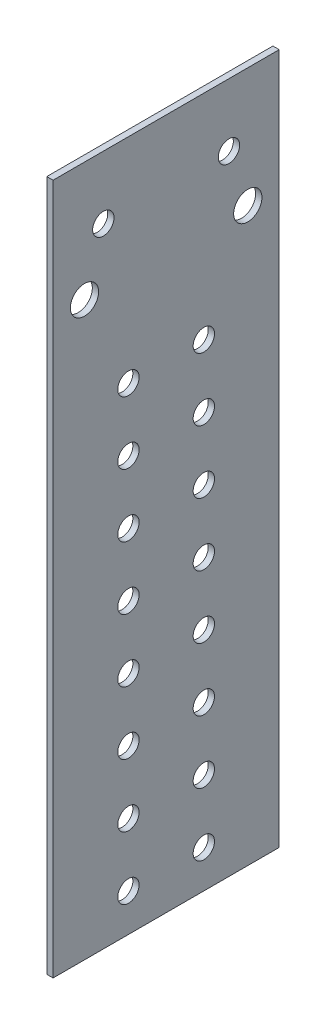
SolidWorks part; units mm, degrees
material "PVC 0.007 Plasticized"
ref_plane "Front Plane" through (0, 0, 0) normal (0, 0, 1) x (1, 0, 0)
ref_plane "Top Plane" through (0, 0, 0) normal (0, 1, 0) x (1, 0, 0)
ref_plane "Right Plane" through (0, 0, 0) normal (1, 0, 0) x (0, 0, -1)
sketch "Sketch1" plane through (0, 0, 0) normal (1, 0, 0) x (0, 0, -1)
  line L1 (-18, 0) -> (18, 0)
  line L2 (-18, 0) -> (-18, -110)
  line L3 (-18, -110) -> (18, -110)
  line L4 (18, 0) -> (18, -110)
  line L5 (-18, 0) -> (18, -110) construction
  line L6 (-18, -110) -> (18, 0) construction
  point P4 (0, -55)
  point P5 (0, 0)
  dimension "D1" = 110
  dimension "D2" = 36
extrude "Boss-Extrude1" add sketch "Sketch1" along normal blind 1 contours L2 L3 L4 L1
hole_wizard "M3 Clearance Hole1" positions "Sketch2" profile "Sketch3" hole size "M3" standard "ISO" end condition through all
sketch "Sketch2" plane through (0, 0, 0) normal (-1, 0, 0) x (0, 0, 1)
  point P0 (-10, -10)
  point P3 (10, -10)
sketch "Sketch3" plane through (0, -10, -10) normal (0, 1, 0) x (0, 0, 1)
  line L0 (0, 0) -> (0, 1)
  line L1 (0, 1) -> (1.7, 1)
  line L2 (1.7, 1) -> (1.7, 0)
  line L5 (1.7, 0) -> (0, 0)
  line L11 (0, -6.35) -> (0, 107.95) construction
  dimension "Thru Hole Dia." = 3.4
  dimension "Thru Hole Depth" = 1
hole_wizard "M4 Clearance Hole1" positions "Sketch4" profile "Sketch5" hole size "M4" standard "ISO" end condition through all
sketch "Sketch4" plane through (0, 0, 0) normal (-1, 0, 0) x (0, 0, 1)
  point P0 (-13, -19)
  point P3 (13, -19)
sketch "Sketch5" plane through (0, -19, -13) normal (0, 1, 0) x (0, 0, 1)
  line L0 (0, 0) -> (0, 1)
  line L1 (0, 1) -> (2.25, 1)
  line L2 (2.25, 1) -> (2.25, 0)
  line L5 (2.25, 0) -> (0, 0)
  line L11 (0, -6.35) -> (0, 107.95) construction
  dimension "Thru Hole Dia." = 4.5
  dimension "Thru Hole Depth" = 1
sketch "Sketch6" plane through (1, 0, 0) normal (1, 0, 0) x (0, 0, -1)
  line L0 (-18, -110) -> (18, -110) construction
  point P0 (-6, -104)
  point P1 (6, -104)
  dimension "D1" = 12
  dimension "D2" = 6
  dimension "D3" = 6
hole_wizard "M3 Clearance Hole2" positions "Sketch7" profile "Sketch8" hole size "M3" standard "ISO" end condition through all
sketch "Sketch7" plane through (1, 0, 0) normal (1, 0, 0) x (0, 0, -1)
  point P0 (6, -104)
  point P3 (-6, -104)
  point P16 (6, -94)
  point P17 (-6, -94)
  point P18 (6, -84)
  point P19 (-6, -84)
  point P20 (6, -74)
  point P21 (-6, -74)
  point P22 (6, -64)
  point P23 (-6, -64)
  point P24 (6, -54)
  point P25 (-6, -54)
  point P26 (6, -44)
  point P27 (-6, -44)
  point P28 (6, -34)
  point P29 (-6, -34)
  dimension "D1" = 8
sketch "Sketch8" plane through (1, -104, -6) normal (0, 1, 0) x (0, 0, -1)
  line L0 (0, 0) -> (0, 1)
  line L1 (0, 1) -> (1.7, 1)
  line L2 (1.7, 1) -> (1.7, 0)
  line L5 (1.7, 0) -> (0, 0)
  line L11 (0, -6.35) -> (0, 107.95) construction
  dimension "Thru Hole Dia." = 3.4
  dimension "Thru Hole Depth" = 1
